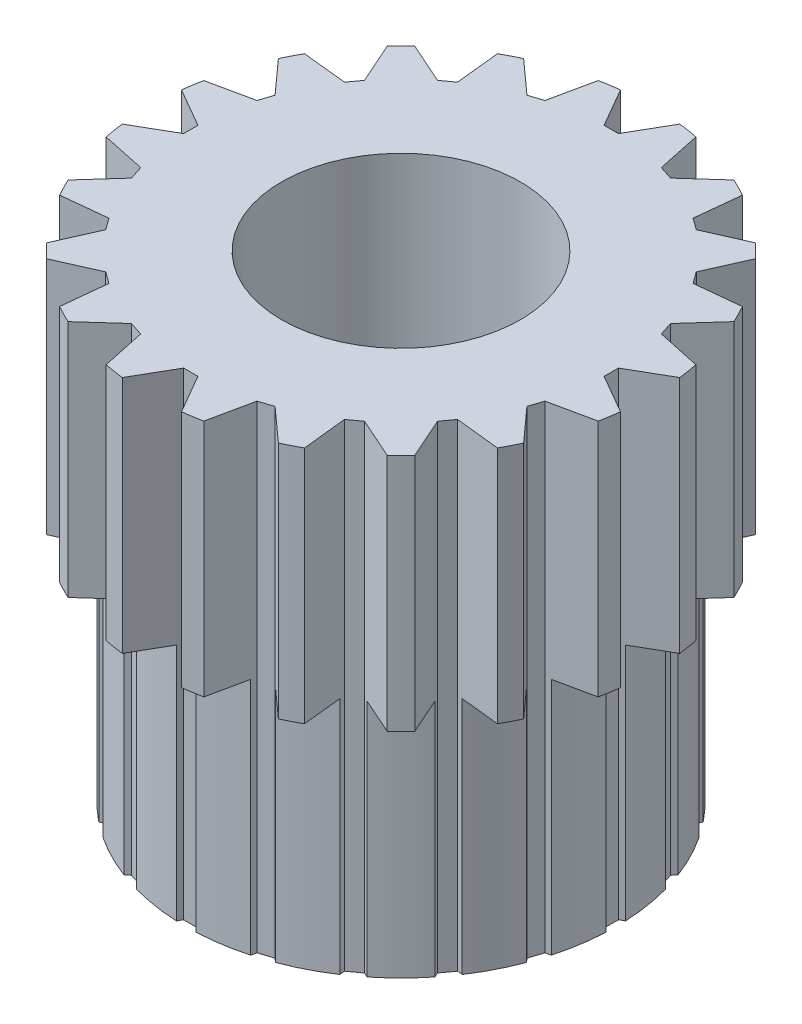
SolidWorks part; units mm, degrees
ref_plane "정면" through (0, 0, 0) normal (0, 0, 1) x (1, 0, 0)
ref_plane "윗면" through (0, 0, 0) normal (0, 1, 0) x (1, 0, 0)
ref_plane "우측면" through (0, 0, 0) normal (1, 0, 0) x (0, 0, -1)
sketch "스케치1" plane through (0, 0, 0) normal (0, 1, 0) x (1, 0, 0)
  circle A0 centre (0, 0) radius 4.5
  dimension "D1" = 9
extrude "보스-돌출1" add sketch "스케치1" along normal blind 10
sketch "스케치2" plane through (0, 10, 0) normal (0, 1, 0) x (1, 0, 0)
  circle A0 centre (0, 0) radius 5.25
  dimension "D1" = 10.5
extrude "보스-돌출2" add sketch "스케치2" against normal blind 5
sketch "스케치4" plane through (0, 10, 0) normal (0, 1, 0) x (1, 0, 0)
  line L0 (0, 0) -> (0, 5.25) construction
  line L1 (0, 4.4) -> (0.15, 4.4)
  line L2 (0.7274, 5.4) -> (0.15, 4.4)
  line L3 (0, 5.4) -> (0, 5.25) construction
  line L4 (0.7274, 5.4) -> (-0.7274, 5.4)
  line L5 (-0.7274, 5.4) -> (-0.15, 4.4)
  line L6 (-0.15, 4.4) -> (0, 4.4)
  circle A0 centre (0, 0) radius 5.25 construction
  dimension "D1" = 4.4
  dimension "D2" = 120
  dimension "D3" = 0.3
extrude "컷-돌출3" cut sketch "스케치4" against normal blind 10
pattern_circular "원형 패턴2" count 20 over 360 about axis through (0, 0, 0) along (0, 1, 0) of "컷-돌출3"
sketch "스케치5" plane through (0, 10, 0) normal (0, 1, 0) x (1, 0, 0)
  circle A0 centre (0, 0) radius 2.5
  dimension "D1" = 5
extrude "컷-돌출4" cut sketch "스케치5" against normal blind 10
